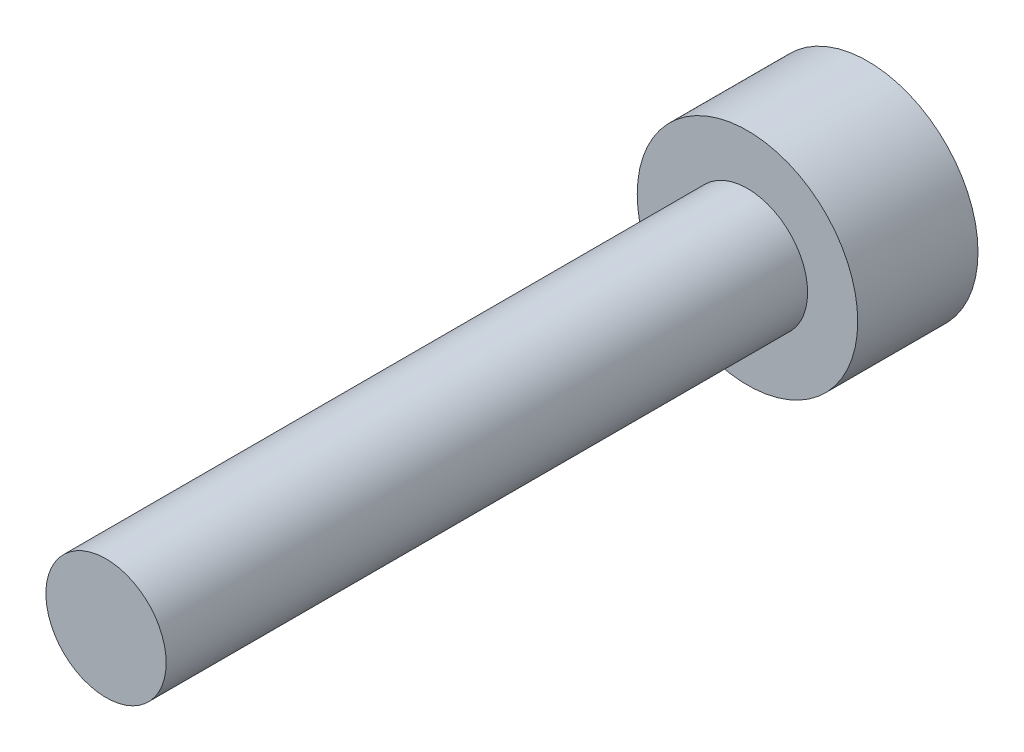
SolidWorks part; units mm, degrees
material "AISI 304"
ref_plane "Alzado" through (0, 0, 0) normal (0, 0, 1) x (1, 0, 0)
ref_plane "Planta" through (0, 0, 0) normal (0, 1, 0) x (1, 0, 0)
ref_plane "Vista lateral" through (0, 0, 0) normal (1, 0, 0) x (0, 0, -1)
sketch "Sk_Cabeza" plane through (0, 0, 0) normal (0, 0, 1) x (1, 0, 0)
  circle A0 centre (0, 0) radius 2.75
  dimension "D1" = 5.5
extrude "Cabeza" add sketch "Sk_Cabeza" along normal blind 3 from offset 3
sketch "Sk_Cuerpo" plane through (0, 0, 0) normal (0, 0, 1) x (1, 0, 0)
  circle A0 centre (0, 0) radius 1.5
  dimension "D1" = 3
extrude "Cuerpo" add sketch "Sk_Cuerpo" along normal blind 16
sketch "Sk_Hexagono_interior" plane through (0, 0, 0) normal (0, 0, 1) x (1, 0, 0)
  line L1 (0, -1.4434) -> (1.25, -0.7217)
  line L2 (1.25, -0.7217) -> (1.25, 0.7217)
  line L3 (1.25, 0.7217) -> (0, 1.4434)
  line L4 (0, 1.4434) -> (-1.25, 0.7217)
  line L5 (-1.25, 0.7217) -> (-1.25, -0.7217)
  line L6 (-1.25, -0.7217) -> (0, -1.4434)
  circle A0 centre (0, 0) radius 1.25 construction
  dimension "D1" = 2.5
extrude "Hexagono_interior" cut sketch "Sk_Hexagono_interior" along normal blind 1.5 from offset 3
